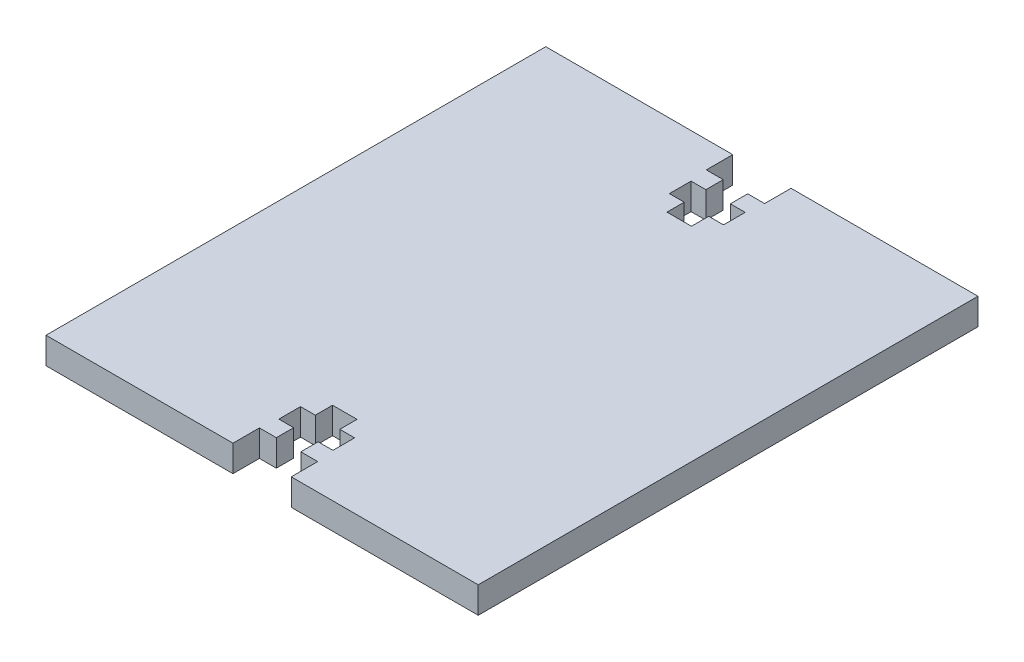
SolidWorks part; units mm, degrees
ref_plane "Front Plane" through (0, 0, 0) normal (0, 0, 1) x (1, 0, 0)
ref_plane "Top Plane" through (0, 0, 0) normal (0, 1, 0) x (1, 0, 0)
ref_plane "Right Plane" through (0, 0, 0) normal (1, 0, 0) x (0, 0, -1)
sketch "Sketch1" plane through (0, 0, 0) normal (0, 1, 0) x (1, 0, 0)
  line L1 (-25.945, 30) -> (25.945, 30)
  line L2 (-25.945, 30) -> (-25.945, -30)
  line L3 (-25.945, -30) -> (25.945, -30)
  line L4 (25.945, 30) -> (25.945, -30)
  line L5 (-25.945, 30) -> (25.945, -30) construction
  line L6 (-25.945, -30) -> (25.945, 30) construction
  point P0 (0, 0)
  dimension "D1" = 51.89
  dimension "D2" = 60
extrude "Boss-Extrude1" add sketch "Sketch1" along normal blind 3.175
sketch "Sketch2" plane through (0, 3.175, 0) normal (0, 1, 0) x (1, 0, 0)
  line L0 (-3.5, 30) -> (3.5, 30)
  line L1 (-3.5, 30) -> (-3.5, 26.825)
  line L2 (-3.5, 26.825) -> (-1.47, 26.825)
  line L3 (3.5, 30) -> (3.5, 26.825)
  line L4 (25.945, 30) -> (-25.945, 30) construction
  line L5 (0, 0) -> (0, 34.4623) construction
  line L6 (0, 22.6456) -> (0, 20.075) construction
  line L7 (1.47, 24.745) -> (3.25, 24.745)
  line L9 (-1.47, 26.825) -> (-1.47, 24.745)
  line L10 (-1.47, 20.075) -> (1.47, 20.075)
  line L11 (1.47, 26.825) -> (1.47, 24.745)
  line L12 (-3.25, 24.745) -> (-1.47, 24.745)
  line L13 (-3.25, 24.745) -> (-3.25, 22.145)
  line L14 (-3.25, 22.145) -> (-1.47, 22.145)
  line L15 (3.25, 24.745) -> (3.25, 22.145)
  line L16 (-1.47, 22.145) -> (-1.47, 20.075)
  line L17 (1.47, 22.145) -> (3.25, 22.145)
  line L18 (1.47, 22.145) -> (1.47, 20.075)
  line L19 (-1.7617, 22.145) -> (2.5367, 22.145) construction
  line L20 (1.47, 26.825) -> (3.5, 26.825)
  line L21 (0, 0) -> (34.4218, 0) construction
  line L22 (1.47, -26.825) -> (1.47, -24.745)
  line L23 (1.47, -24.745) -> (3.25, -24.745)
  line L24 (3.25, -24.745) -> (3.25, -22.145)
  line L25 (1.47, -22.145) -> (3.25, -22.145)
  line L26 (1.47, -22.145) -> (1.47, -20.075)
  line L27 (-1.47, -20.075) -> (1.47, -20.075)
  line L28 (-1.47, -22.145) -> (-1.47, -20.075)
  line L29 (-3.25, -22.145) -> (-1.47, -22.145)
  line L30 (-3.25, -24.745) -> (-3.25, -22.145)
  line L31 (-3.25, -24.745) -> (-1.47, -24.745)
  line L32 (-1.47, -26.825) -> (-1.47, -24.745)
  line L33 (-3.5, -26.825) -> (-1.47, -26.825)
  line L34 (-3.5, -30) -> (-3.5, -26.825)
  line L35 (-3.5, -30) -> (3.5, -30)
  line L36 (3.5, -30) -> (3.5, -26.825)
  line L37 (1.47, -26.825) -> (3.5, -26.825)
  dimension "D1" = 7
  dimension "D2" = 6.5
  dimension "D3" = 2.94
  dimension "D4" = 6.75
  dimension "D5" = 2.08
  dimension "D6" = 3.175
  dimension "D7" = 2.6
extrude "Cut-Extrude1" cut sketch "Sketch2" against normal blind 10
